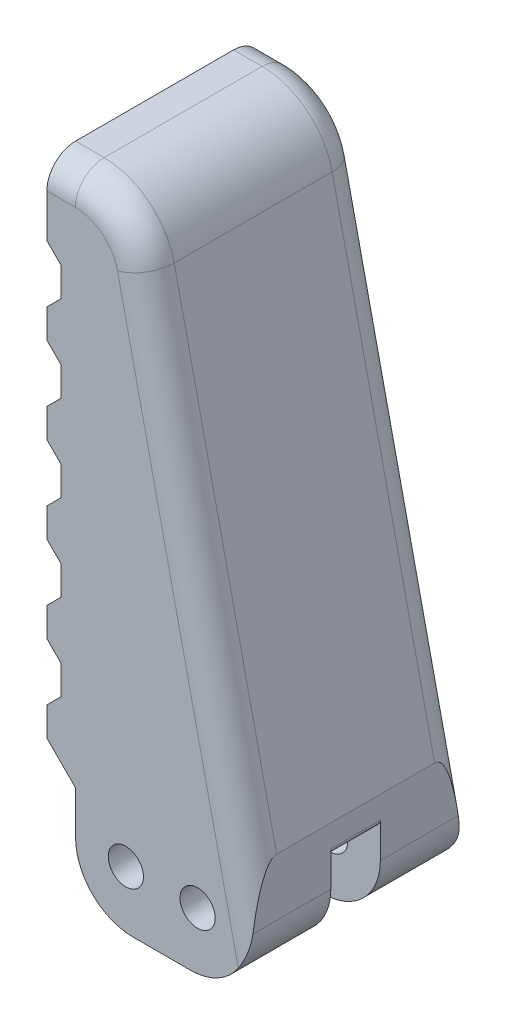
SolidWorks part; units mm, degrees
material "ABS"
ref_plane "Front Plane" through (0, 0, 0) normal (0, 0, 1) x (1, 0, 0)
ref_plane "Top Plane" through (0, 0, 0) normal (0, 1, 0) x (1, 0, 0)
ref_plane "Right Plane" through (0, 0, 0) normal (1, 0, 0) x (0, 0, -1)
sketch "Sketch1" plane through (0, 0, 0) normal (0, 0, 1) x (1, 0, 0)
  line L0 (0, 0) -> (0, 40) construction
  line L1 (-6, -4) -> (6, -4)
  line L2 (-6, -4) -> (-6, 40)
  line L3 (-6, 40) -> (-2, 40)
  line L4 (6, -4) -> (6, 4)
  line L5 (-2, 40) -> (6, 4)
  line L6 (-2.5, 0) -> (2.5, 0) construction
  circle A0 centre (-2.5, 0) radius 1.225
  circle A1 centre (2.5, 0) radius 1.225
  dimension "D2" = 2.45
  dimension "D1" = 5
  dimension "D3" = 40
  dimension "D4" = 12
  dimension "D5" = 4
  dimension "D7" = 4
extrude "Boss-Extrude1" add sketch "Sketch1" along normal mid plane 15
sketch "Sketch4" plane through (0, 0, 0) normal (0, 0, 1) x (1, 0, 0)
  line L1 (-3.05, 3) -> (3.05, 3)
  line L2 (-6.5, -0.45) -> (-6.5, -4)
  line L3 (-6.5, -4) -> (6.5, -4)
  line L4 (6.5, -0.45) -> (6.5, -4)
  line L5 (0, 0) -> (0, -4) construction
  line L6 (-6, -4) -> (6, -4) construction
  arc A0 (6.5, -0.45) -> (3.05, 3) centre (3.05, -0.45) ccw
  arc A1 (-3.05, 3) -> (-6.5, -0.45) centre (-3.05, -0.45) ccw
  point P8 (6.5, 3)
  dimension "D2" = 3.45
  dimension "D1" = 7
  dimension "D3" = 13
extrude "Cut-Extrude2" cut sketch "Sketch4" against normal mid plane 3.45
sketch "Sketch6" plane through (0, 0, 0) normal (0, 0, 1) x (1, 0, 0)
  line L0 (-6, 40) -> (-6, 3)
  line L2 (-6, 40) -> (-6, -4) construction
  line L3 (-8, 5) -> (-8, 7)
  line L4 (-8, 7) -> (-7, 8)
  line L5 (-7, 8) -> (-7, 10)
  line L6 (-7, 10) -> (-8, 11)
  line L7 (-8, 13) -> (-7, 14)
  line L8 (-7, 14) -> (-7, 16)
  line L9 (-7, 16) -> (-8, 17)
  line L10 (-8, 19) -> (-7, 20)
  line L11 (-7, 20) -> (-7, 22)
  line L12 (-7, 22) -> (-8, 23)
  line L13 (-8, 25) -> (-7, 26)
  line L14 (-7, 26) -> (-7, 28)
  line L15 (-7, 28) -> (-8, 29)
  line L16 (-8, 31) -> (-7, 32)
  line L17 (-7, 32) -> (-7, 34)
  line L18 (-7, 34) -> (-8, 35)
  line L19 (-8, 11) -> (-8, 13)
  line L20 (-8, 17) -> (-8, 19)
  line L21 (-8, 23) -> (-8, 25)
  line L22 (-8, 29) -> (-8, 31)
  line L23 (-8, 35) -> (-8, 40)
  line L24 (-8, 40) -> (-6, 40)
  line L25 (-8, 5) -> (-6, 3)
  dimension "D1" = 3
  dimension "D2" = 2
  dimension "D3" = 1
  dimension "D4" = 2
  dimension "D6" = 2
  dimension "D5" = 5
extrude "Boss-Extrude3" add sketch "Sketch6" along normal up to surface and the other way up to surface up to face at (-1.275, 0, 7.5) other way up to face at (-1.275, 0, -7.5)
fillet "Fillet5" radius 5 1 edges at (-2, 40, 0)
fillet "Fillet6" radius 4 4 edges at (6, -4, -4.6125) (6, -4, 4.6125) (-6, -4, -4.6125) (-6, -4, 4.6125)
fillet "Fillet7" radius 2 6 edges at (-2.8822, 38.9002, -7.5) (-2.8822, 38.9002, 7.5) (2.435, 20.0423, -7.5) (2.435, 20.0423, 7.5) (-7.0054, 40, -7.5) (-7.0054, 40, 7.5)
fillet "Fillet8" radius 0.4 2 edges at (6, 1.3389, 0) (-6, 1.3389, 0)
equation "\"D2@Sketch1\"=2.00mm+\"print_free@Parameters@FabricationParameters.sldprt\""
equation "\"D2@Sketch4\"=3.00mm+\"print_free@Parameters@FabricationParameters.sldprt\""
equation "\"D1@Cut-Extrude2\"=3.00mm+\"print_free@Parameters@FabricationParameters.sldprt\""
